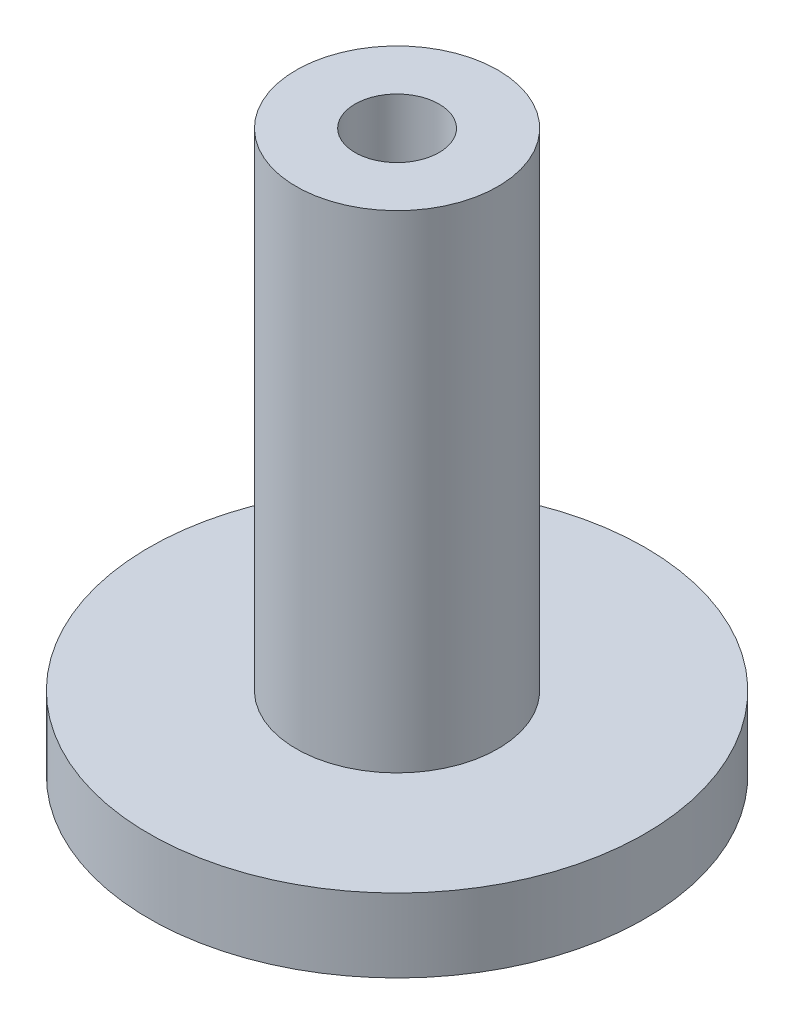
SolidWorks part; units mm, degrees
material "ABS"
ref_plane "Front Plane" through (0, 0, 0) normal (0, 0, 1) x (1, 0, 0)
ref_plane "Top Plane" through (0, 0, 0) normal (0, 1, 0) x (1, 0, 0)
ref_plane "Right Plane" through (0, 0, 0) normal (1, 0, 0) x (0, 0, -1)
sketch "Sketch1" plane through (0, 0, 0) normal (0, 0, 1) x (1, 0, 0)
  line L0 (-1.143, 0) -> (-1.143, 15.24)
  line L1 (-1.143, 15.24) -> (-2.743, 15.24)
  line L2 (-2.743, 15.24) -> (-2.743, 2)
  line L3 (-2.743, 2) -> (-6.743, 2)
  line L4 (-6.743, 2) -> (-6.743, 0)
  line L5 (-6.743, 0) -> (-1.143, 0)
  line L6 (0, 0) -> (0, 4.7094) construction
  dimension "D1" = 1.143
  dimension "D2" = 15.24
  dimension "D3" = 1.6
  dimension "D4" = 2
  dimension "D5" = 4
revolve "Revolve1" add sketch "Sketch1" angle 360 about L6
